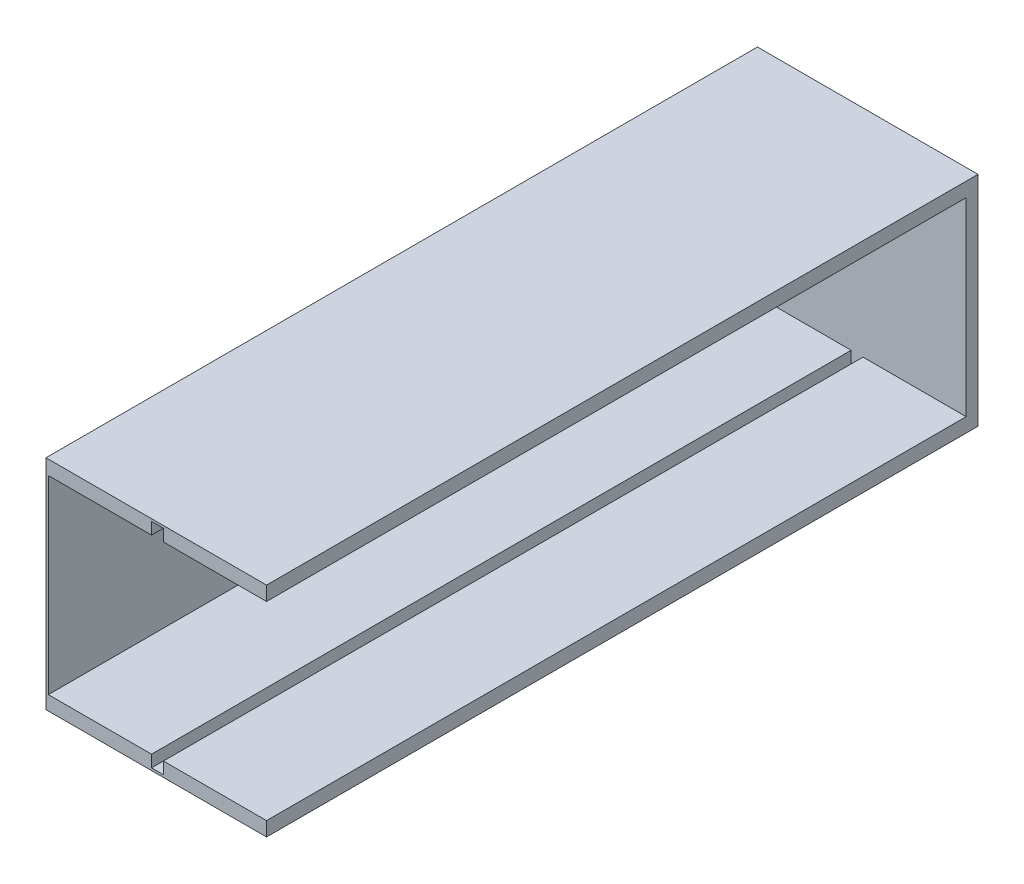
SolidWorks part; units mm, degrees
ref_plane "Front Plane" through (0, 0, 0) normal (0, 0, 1) x (1, 0, 0)
ref_plane "Top Plane" through (0, 0, 0) normal (0, 1, 0) x (1, 0, 0)
ref_plane "Right Plane" through (0, 0, 0) normal (1, 0, 0) x (0, 0, -1)
sketch "Sketch1" plane through (0, 0, 0) normal (0, 0, 1) x (1, 0, 0)
  line L0 (0, -30) -> (217.5, -30)
  line L1 (0, 0) -> (460, 0)
  line L4 (460, 0) -> (460, -30)
  line L5 (217.5, -30) -> (217.5, -5)
  line L6 (217.5, -5) -> (242.5, -5)
  line L7 (242.5, -5) -> (242.5, -30)
  line L8 (242.5, -30) -> (460, -30)
  line L22 (230, 0) -> (230, -460) construction
  line L23 (521.7993, -230) -> (230, -230) construction
  line L39 (242.5, -430) -> (460, -430)
  line L40 (242.5, -455) -> (242.5, -430)
  line L41 (217.5, -455) -> (242.5, -455)
  line L42 (217.5, -430) -> (217.5, -455)
  line L43 (460, -460) -> (460, -430)
  line L44 (0, -460) -> (460, -460)
  line L45 (0, -430) -> (217.5, -430)
  line L46 (0, -460) -> (0, -430)
  line L47 (0, -30) -> (0, 0)
  dimension "D1" = 460
  dimension "D2" = 460
  dimension "D3" = 25
  dimension "D4" = 217.5
  dimension "D5" = 25
  dimension "D6" = 25
  dimension "D7" = 5
extrude "Boss-Extrude1" add sketch "Sketch1" along normal blind 1500
sketch "Sketch5" plane through (0, 0, 0) normal (0, 0, -1) x (-1, 0, 0)
  line L5 (0, 0) -> (-460, 0)
  line L6 (0, 0) -> (0, -460)
  line L7 (0, -460) -> (-460, -460)
  line L8 (-460, 0) -> (-460, -460)
extrude "Boss-Extrude5" add sketch "Sketch5" against normal blind 25
sketch "Sketch6" plane through (0, 0, 0) normal (-1, 0, 0) x (0, 0, 1)
  line L1 (1500, 0) -> (0, 0)
  line L2 (1500, 0) -> (1500, -460)
  line L3 (1500, -460) -> (0, -460)
  line L4 (0, 0) -> (0, -460)
extrude "Boss-Extrude6" add sketch "Sketch6" along normal blind 5
